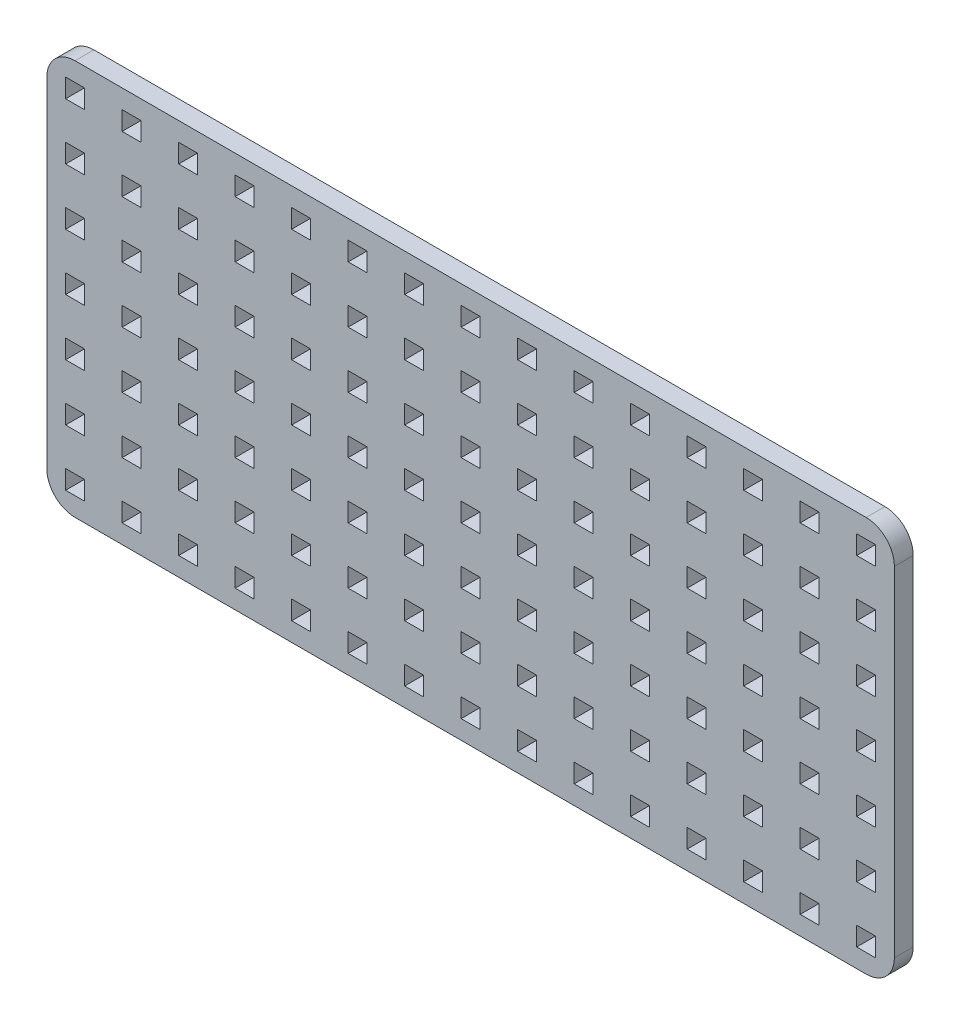
SolidWorks part; units mm, degrees
ref_plane "Alzado" through (0, 0, 0) normal (0, 0, 1) x (1, 0, 0)
ref_plane "Planta" through (0, 0, 0) normal (0, 1, 0) x (1, 0, 0)
ref_plane "Vista lateral" through (0, 0, 0) normal (1, 0, 0) x (0, 0, -1)
sketch "Model" plane through (0, 0, 0) normal (0, 0, 1) x (1, 0, 0)
  line L0 (11.9912, 291.2013) -> (11.9912, 288.2013)
  line L1 (14.9912, 291.2013) -> (11.9912, 291.2013)
  line L2 (14.9912, 288.2013) -> (14.9912, 291.2013)
  line L3 (11.9912, 288.2013) -> (14.9912, 288.2013)
  line L4 (20.9912, 291.2013) -> (20.9912, 288.2013)
  line L5 (23.9912, 291.2013) -> (20.9912, 291.2013)
  line L6 (23.9912, 288.2013) -> (23.9912, 291.2013)
  line L7 (20.9912, 288.2013) -> (23.9912, 288.2013)
  line L8 (29.9912, 291.2013) -> (29.9912, 288.2013)
  line L9 (32.9912, 291.2013) -> (29.9912, 291.2013)
  line L10 (32.9912, 288.2013) -> (32.9912, 291.2013)
  line L11 (29.9912, 288.2013) -> (32.9912, 288.2013)
  line L12 (38.9912, 291.2013) -> (38.9912, 288.2013)
  line L13 (41.9912, 291.2013) -> (38.9912, 291.2013)
  line L14 (41.9912, 288.2013) -> (41.9912, 291.2013)
  line L15 (38.9912, 288.2013) -> (41.9912, 288.2013)
  line L16 (47.9912, 291.2013) -> (47.9912, 288.2013)
  line L17 (50.9912, 291.2013) -> (47.9912, 291.2013)
  line L18 (50.9912, 288.2013) -> (50.9912, 291.2013)
  line L19 (47.9912, 288.2013) -> (50.9912, 288.2013)
  line L20 (56.9912, 291.2013) -> (56.9912, 288.2013)
  line L21 (59.9912, 291.2013) -> (56.9912, 291.2013)
  line L22 (59.9912, 288.2013) -> (59.9912, 291.2013)
  line L23 (56.9912, 288.2013) -> (59.9912, 288.2013)
  line L24 (65.9912, 291.2013) -> (65.9912, 288.2013)
  line L25 (68.9912, 291.2013) -> (65.9912, 291.2013)
  line L26 (68.9912, 288.2013) -> (68.9912, 291.2013)
  line L27 (65.9912, 288.2013) -> (68.9912, 288.2013)
  line L28 (74.9912, 291.2013) -> (74.9912, 288.2013)
  line L29 (77.9912, 291.2013) -> (74.9912, 291.2013)
  line L30 (77.9912, 288.2013) -> (77.9912, 291.2013)
  line L31 (74.9912, 288.2013) -> (77.9912, 288.2013)
  line L32 (83.9912, 291.2013) -> (83.9912, 288.2013)
  line L33 (86.9912, 291.2013) -> (83.9912, 291.2013)
  line L34 (86.9912, 288.2013) -> (86.9912, 291.2013)
  line L35 (83.9912, 288.2013) -> (86.9912, 288.2013)
  line L36 (92.9912, 291.2013) -> (92.9912, 288.2013)
  line L37 (95.9912, 291.2013) -> (92.9912, 291.2013)
  line L38 (95.9912, 288.2013) -> (95.9912, 291.2013)
  line L39 (92.9912, 288.2013) -> (95.9912, 288.2013)
  line L40 (101.9912, 291.2013) -> (101.9912, 288.2013)
  line L41 (104.9912, 291.2013) -> (101.9912, 291.2013)
  line L42 (104.9912, 288.2013) -> (104.9912, 291.2013)
  line L43 (101.9912, 288.2013) -> (104.9912, 288.2013)
  line L44 (110.9912, 291.2013) -> (110.9912, 288.2013)
  line L45 (113.9912, 291.2013) -> (110.9912, 291.2013)
  line L46 (113.9912, 288.2013) -> (113.9912, 291.2013)
  line L47 (110.9912, 288.2013) -> (113.9912, 288.2013)
  line L48 (119.9912, 291.2013) -> (119.9912, 288.2013)
  line L49 (122.9912, 291.2013) -> (119.9912, 291.2013)
  line L50 (122.9912, 288.2013) -> (122.9912, 291.2013)
  line L51 (119.9912, 288.2013) -> (122.9912, 288.2013)
  line L52 (128.9912, 291.2013) -> (128.9912, 288.2013)
  line L53 (131.9912, 291.2013) -> (128.9912, 291.2013)
  line L54 (131.9912, 288.2013) -> (131.9912, 291.2013)
  line L55 (128.9912, 288.2013) -> (131.9912, 288.2013)
  line L56 (137.9912, 291.2013) -> (137.9912, 288.2013)
  line L57 (140.9912, 291.2013) -> (137.9912, 291.2013)
  line L58 (140.9912, 288.2013) -> (140.9912, 291.2013)
  line L59 (137.9912, 288.2013) -> (140.9912, 288.2013)
  line L60 (11.9912, 282.2013) -> (11.9912, 279.2013)
  line L61 (14.9912, 282.2013) -> (11.9912, 282.2013)
  line L62 (14.9912, 279.2013) -> (14.9912, 282.2013)
  line L63 (11.9912, 279.2013) -> (14.9912, 279.2013)
  line L64 (20.9912, 282.2013) -> (20.9912, 279.2013)
  line L65 (23.9912, 282.2013) -> (20.9912, 282.2013)
  line L66 (23.9912, 279.2013) -> (23.9912, 282.2013)
  line L67 (20.9912, 279.2013) -> (23.9912, 279.2013)
  line L68 (29.9912, 282.2013) -> (29.9912, 279.2013)
  line L69 (32.9912, 282.2013) -> (29.9912, 282.2013)
  line L70 (32.9912, 279.2013) -> (32.9912, 282.2013)
  line L71 (29.9912, 279.2013) -> (32.9912, 279.2013)
  line L72 (38.9912, 282.2013) -> (38.9912, 279.2013)
  line L73 (41.9912, 282.2013) -> (38.9912, 282.2013)
  line L74 (41.9912, 279.2013) -> (41.9912, 282.2013)
  line L75 (38.9912, 279.2013) -> (41.9912, 279.2013)
  line L76 (47.9912, 282.2013) -> (47.9912, 279.2013)
  line L77 (50.9912, 282.2013) -> (47.9912, 282.2013)
  line L78 (50.9912, 279.2013) -> (50.9912, 282.2013)
  line L79 (47.9912, 279.2013) -> (50.9912, 279.2013)
  line L80 (56.9912, 282.2013) -> (56.9912, 279.2013)
  line L81 (59.9912, 282.2013) -> (56.9912, 282.2013)
  line L82 (59.9912, 279.2013) -> (59.9912, 282.2013)
  line L83 (56.9912, 279.2013) -> (59.9912, 279.2013)
  line L84 (65.9912, 282.2013) -> (65.9912, 279.2013)
  line L85 (68.9912, 282.2013) -> (65.9912, 282.2013)
  line L86 (68.9912, 279.2013) -> (68.9912, 282.2013)
  line L87 (65.9912, 279.2013) -> (68.9912, 279.2013)
  line L88 (74.9912, 282.2013) -> (74.9912, 279.2013)
  line L89 (77.9912, 282.2013) -> (74.9912, 282.2013)
  line L90 (77.9912, 279.2013) -> (77.9912, 282.2013)
  line L91 (74.9912, 279.2013) -> (77.9912, 279.2013)
  line L92 (83.9912, 282.2013) -> (83.9912, 279.2013)
  line L93 (86.9912, 282.2013) -> (83.9912, 282.2013)
  line L94 (86.9912, 279.2013) -> (86.9912, 282.2013)
  line L95 (83.9912, 279.2013) -> (86.9912, 279.2013)
  line L96 (92.9912, 282.2013) -> (92.9912, 279.2013)
  line L97 (95.9912, 282.2013) -> (92.9912, 282.2013)
  line L98 (95.9912, 279.2013) -> (95.9912, 282.2013)
  line L99 (92.9912, 279.2013) -> (95.9912, 279.2013)
  line L100 (101.9912, 282.2013) -> (101.9912, 279.2013)
  line L101 (104.9912, 282.2013) -> (101.9912, 282.2013)
  line L102 (104.9912, 279.2013) -> (104.9912, 282.2013)
  line L103 (101.9912, 279.2013) -> (104.9912, 279.2013)
  line L104 (110.9912, 282.2013) -> (110.9912, 279.2013)
  line L105 (113.9912, 282.2013) -> (110.9912, 282.2013)
  line L106 (113.9912, 279.2013) -> (113.9912, 282.2013)
  line L107 (110.9912, 279.2013) -> (113.9912, 279.2013)
  line L108 (119.9912, 282.2013) -> (119.9912, 279.2013)
  line L109 (122.9912, 282.2013) -> (119.9912, 282.2013)
  line L110 (122.9912, 279.2013) -> (122.9912, 282.2013)
  line L111 (119.9912, 279.2013) -> (122.9912, 279.2013)
  line L112 (128.9912, 282.2013) -> (128.9912, 279.2013)
  line L113 (131.9912, 282.2013) -> (128.9912, 282.2013)
  line L114 (131.9912, 279.2013) -> (131.9912, 282.2013)
  line L115 (128.9912, 279.2013) -> (131.9912, 279.2013)
  line L116 (137.9912, 282.2013) -> (137.9912, 279.2013)
  line L117 (140.9912, 282.2013) -> (137.9912, 282.2013)
  line L118 (140.9912, 279.2013) -> (140.9912, 282.2013)
  line L119 (137.9912, 279.2013) -> (140.9912, 279.2013)
  line L120 (11.9912, 273.2013) -> (11.9912, 270.2013)
  line L121 (14.9912, 273.2013) -> (11.9912, 273.2013)
  line L122 (14.9912, 270.2013) -> (14.9912, 273.2013)
  line L123 (11.9912, 270.2013) -> (14.9912, 270.2013)
  line L124 (20.9912, 273.2013) -> (20.9912, 270.2013)
  line L125 (23.9912, 273.2013) -> (20.9912, 273.2013)
  line L126 (23.9912, 270.2013) -> (23.9912, 273.2013)
  line L127 (20.9912, 270.2013) -> (23.9912, 270.2013)
  line L128 (29.9912, 273.2013) -> (29.9912, 270.2013)
  line L129 (32.9912, 273.2013) -> (29.9912, 273.2013)
  line L130 (32.9912, 270.2013) -> (32.9912, 273.2013)
  line L131 (29.9912, 270.2013) -> (32.9912, 270.2013)
  line L132 (38.9912, 273.2013) -> (38.9912, 270.2013)
  line L133 (41.9912, 273.2013) -> (38.9912, 273.2013)
  line L134 (41.9912, 270.2013) -> (41.9912, 273.2013)
  line L135 (38.9912, 270.2013) -> (41.9912, 270.2013)
  line L136 (47.9912, 273.2013) -> (47.9912, 270.2013)
  line L137 (50.9912, 273.2013) -> (47.9912, 273.2013)
  line L138 (50.9912, 270.2013) -> (50.9912, 273.2013)
  line L139 (47.9912, 270.2013) -> (50.9912, 270.2013)
  line L140 (56.9912, 273.2013) -> (56.9912, 270.2013)
  line L141 (59.9912, 273.2013) -> (56.9912, 273.2013)
  line L142 (59.9912, 270.2013) -> (59.9912, 273.2013)
  line L143 (56.9912, 270.2013) -> (59.9912, 270.2013)
  line L144 (65.9912, 273.2013) -> (65.9912, 270.2013)
  line L145 (68.9912, 273.2013) -> (65.9912, 273.2013)
  line L146 (68.9912, 270.2013) -> (68.9912, 273.2013)
  line L147 (65.9912, 270.2013) -> (68.9912, 270.2013)
  line L148 (74.9912, 273.2013) -> (74.9912, 270.2013)
  line L149 (77.9912, 273.2013) -> (74.9912, 273.2013)
  line L150 (77.9912, 270.2013) -> (77.9912, 273.2013)
  line L151 (74.9912, 270.2013) -> (77.9912, 270.2013)
  line L152 (83.9912, 273.2013) -> (83.9912, 270.2013)
  line L153 (86.9912, 273.2013) -> (83.9912, 273.2013)
  line L154 (86.9912, 270.2013) -> (86.9912, 273.2013)
  line L155 (83.9912, 270.2013) -> (86.9912, 270.2013)
  line L156 (92.9912, 273.2013) -> (92.9912, 270.2013)
  line L157 (95.9912, 273.2013) -> (92.9912, 273.2013)
  line L158 (95.9912, 270.2013) -> (95.9912, 273.2013)
  line L159 (92.9912, 270.2013) -> (95.9912, 270.2013)
  line L160 (101.9912, 273.2013) -> (101.9912, 270.2013)
  line L161 (104.9912, 273.2013) -> (101.9912, 273.2013)
  line L162 (104.9912, 270.2013) -> (104.9912, 273.2013)
  line L163 (101.9912, 270.2013) -> (104.9912, 270.2013)
  line L164 (110.9912, 273.2013) -> (110.9912, 270.2013)
  line L165 (113.9912, 273.2013) -> (110.9912, 273.2013)
  line L166 (113.9912, 270.2013) -> (113.9912, 273.2013)
  line L167 (110.9912, 270.2013) -> (113.9912, 270.2013)
  line L168 (119.9912, 273.2013) -> (119.9912, 270.2013)
  line L169 (122.9912, 273.2013) -> (119.9912, 273.2013)
  line L170 (122.9912, 270.2013) -> (122.9912, 273.2013)
  line L171 (119.9912, 270.2013) -> (122.9912, 270.2013)
  line L172 (128.9912, 273.2013) -> (128.9912, 270.2013)
  line L173 (131.9912, 273.2013) -> (128.9912, 273.2013)
  line L174 (131.9912, 270.2013) -> (131.9912, 273.2013)
  line L175 (128.9912, 270.2013) -> (131.9912, 270.2013)
  line L176 (137.9912, 273.2013) -> (137.9912, 270.2013)
  line L177 (140.9912, 273.2013) -> (137.9912, 273.2013)
  line L178 (140.9912, 270.2013) -> (140.9912, 273.2013)
  line L179 (137.9912, 270.2013) -> (140.9912, 270.2013)
  line L180 (11.9912, 264.2013) -> (11.9912, 261.2013)
  line L181 (14.9912, 264.2013) -> (11.9912, 264.2013)
  line L182 (14.9912, 261.2013) -> (14.9912, 264.2013)
  line L183 (11.9912, 261.2013) -> (14.9912, 261.2013)
  line L184 (20.9912, 264.2013) -> (20.9912, 261.2013)
  line L185 (23.9912, 264.2013) -> (20.9912, 264.2013)
  line L186 (23.9912, 261.2013) -> (23.9912, 264.2013)
  line L187 (20.9912, 261.2013) -> (23.9912, 261.2013)
  line L188 (29.9912, 264.2013) -> (29.9912, 261.2013)
  line L189 (32.9912, 264.2013) -> (29.9912, 264.2013)
  line L190 (32.9912, 261.2013) -> (32.9912, 264.2013)
  line L191 (29.9912, 261.2013) -> (32.9912, 261.2013)
  line L192 (38.9912, 264.2013) -> (38.9912, 261.2013)
  line L193 (41.9912, 264.2013) -> (38.9912, 264.2013)
  line L194 (41.9912, 261.2013) -> (41.9912, 264.2013)
  line L195 (38.9912, 261.2013) -> (41.9912, 261.2013)
  line L196 (47.9912, 264.2013) -> (47.9912, 261.2013)
  line L197 (50.9912, 264.2013) -> (47.9912, 264.2013)
  line L198 (50.9912, 261.2013) -> (50.9912, 264.2013)
  line L199 (47.9912, 261.2013) -> (50.9912, 261.2013)
  line L200 (56.9912, 264.2013) -> (56.9912, 261.2013)
  line L201 (59.9912, 264.2013) -> (56.9912, 264.2013)
  line L202 (59.9912, 261.2013) -> (59.9912, 264.2013)
  line L203 (56.9912, 261.2013) -> (59.9912, 261.2013)
  line L204 (65.9912, 264.2013) -> (65.9912, 261.2013)
  line L205 (68.9912, 264.2013) -> (65.9912, 264.2013)
  line L206 (68.9912, 261.2013) -> (68.9912, 264.2013)
  line L207 (65.9912, 261.2013) -> (68.9912, 261.2013)
  line L208 (74.9912, 264.2013) -> (74.9912, 261.2013)
  line L209 (77.9912, 264.2013) -> (74.9912, 264.2013)
  line L210 (77.9912, 261.2013) -> (77.9912, 264.2013)
  line L211 (74.9912, 261.2013) -> (77.9912, 261.2013)
  line L212 (83.9912, 264.2013) -> (83.9912, 261.2013)
  line L213 (86.9912, 264.2013) -> (83.9912, 264.2013)
  line L214 (86.9912, 261.2013) -> (86.9912, 264.2013)
  line L215 (83.9912, 261.2013) -> (86.9912, 261.2013)
  line L216 (92.9912, 264.2013) -> (92.9912, 261.2013)
  line L217 (95.9912, 264.2013) -> (92.9912, 264.2013)
  line L218 (95.9912, 261.2013) -> (95.9912, 264.2013)
  line L219 (92.9912, 261.2013) -> (95.9912, 261.2013)
  line L220 (101.9912, 264.2013) -> (101.9912, 261.2013)
  line L221 (104.9912, 264.2013) -> (101.9912, 264.2013)
  line L222 (104.9912, 261.2013) -> (104.9912, 264.2013)
  line L223 (101.9912, 261.2013) -> (104.9912, 261.2013)
  line L224 (110.9912, 264.2013) -> (110.9912, 261.2013)
  line L225 (113.9912, 264.2013) -> (110.9912, 264.2013)
  line L226 (113.9912, 261.2013) -> (113.9912, 264.2013)
  line L227 (110.9912, 261.2013) -> (113.9912, 261.2013)
  line L228 (119.9912, 264.2013) -> (119.9912, 261.2013)
  line L229 (122.9912, 264.2013) -> (119.9912, 264.2013)
  line L230 (122.9912, 261.2013) -> (122.9912, 264.2013)
  line L231 (119.9912, 261.2013) -> (122.9912, 261.2013)
  line L232 (128.9912, 264.2013) -> (128.9912, 261.2013)
  line L233 (131.9912, 264.2013) -> (128.9912, 264.2013)
  line L234 (131.9912, 261.2013) -> (131.9912, 264.2013)
  line L235 (128.9912, 261.2013) -> (131.9912, 261.2013)
  line L236 (137.9912, 264.2013) -> (137.9912, 261.2013)
  line L237 (140.9912, 264.2013) -> (137.9912, 264.2013)
  line L238 (140.9912, 261.2013) -> (140.9912, 264.2013)
  line L239 (137.9912, 261.2013) -> (140.9912, 261.2013)
  line L240 (11.9912, 255.2013) -> (11.9912, 252.2013)
  line L241 (14.9912, 255.2013) -> (11.9912, 255.2013)
  line L242 (14.9912, 252.2013) -> (14.9912, 255.2013)
  line L243 (11.9912, 252.2013) -> (14.9912, 252.2013)
  line L244 (20.9912, 255.2013) -> (20.9912, 252.2013)
  line L245 (23.9912, 255.2013) -> (20.9912, 255.2013)
  line L246 (23.9912, 252.2013) -> (23.9912, 255.2013)
  line L247 (20.9912, 252.2013) -> (23.9912, 252.2013)
  line L248 (29.9912, 255.2013) -> (29.9912, 252.2013)
  line L249 (32.9912, 255.2013) -> (29.9912, 255.2013)
  line L250 (32.9912, 252.2013) -> (32.9912, 255.2013)
  line L251 (29.9912, 252.2013) -> (32.9912, 252.2013)
  line L252 (38.9912, 255.2013) -> (38.9912, 252.2013)
  line L253 (41.9912, 255.2013) -> (38.9912, 255.2013)
  line L254 (41.9912, 252.2013) -> (41.9912, 255.2013)
  line L255 (38.9912, 252.2013) -> (41.9912, 252.2013)
  line L256 (47.9912, 255.2013) -> (47.9912, 252.2013)
  line L257 (50.9912, 255.2013) -> (47.9912, 255.2013)
  line L258 (50.9912, 252.2013) -> (50.9912, 255.2013)
  line L259 (47.9912, 252.2013) -> (50.9912, 252.2013)
  line L260 (56.9912, 255.2013) -> (56.9912, 252.2013)
  line L261 (59.9912, 255.2013) -> (56.9912, 255.2013)
  line L262 (59.9912, 252.2013) -> (59.9912, 255.2013)
  line L263 (56.9912, 252.2013) -> (59.9912, 252.2013)
  line L264 (65.9912, 255.2013) -> (65.9912, 252.2013)
  line L265 (68.9912, 255.2013) -> (65.9912, 255.2013)
  line L266 (68.9912, 252.2013) -> (68.9912, 255.2013)
  line L267 (65.9912, 252.2013) -> (68.9912, 252.2013)
  line L268 (74.9912, 255.2013) -> (74.9912, 252.2013)
  line L269 (77.9912, 255.2013) -> (74.9912, 255.2013)
  line L270 (77.9912, 252.2013) -> (77.9912, 255.2013)
  line L271 (74.9912, 252.2013) -> (77.9912, 252.2013)
  line L272 (83.9912, 255.2013) -> (83.9912, 252.2013)
  line L273 (86.9912, 255.2013) -> (83.9912, 255.2013)
  line L274 (86.9912, 252.2013) -> (86.9912, 255.2013)
  line L275 (83.9912, 252.2013) -> (86.9912, 252.2013)
  line L276 (92.9912, 255.2013) -> (92.9912, 252.2013)
  line L277 (95.9912, 255.2013) -> (92.9912, 255.2013)
  line L278 (95.9912, 252.2013) -> (95.9912, 255.2013)
  line L279 (92.9912, 252.2013) -> (95.9912, 252.2013)
  line L280 (101.9912, 255.2013) -> (101.9912, 252.2013)
  line L281 (104.9912, 255.2013) -> (101.9912, 255.2013)
  line L282 (104.9912, 252.2013) -> (104.9912, 255.2013)
  line L283 (101.9912, 252.2013) -> (104.9912, 252.2013)
  line L284 (110.9912, 255.2013) -> (110.9912, 252.2013)
  line L285 (113.9912, 255.2013) -> (110.9912, 255.2013)
  line L286 (113.9912, 252.2013) -> (113.9912, 255.2013)
  line L287 (110.9912, 252.2013) -> (113.9912, 252.2013)
  line L288 (119.9912, 255.2013) -> (119.9912, 252.2013)
  line L289 (122.9912, 255.2013) -> (119.9912, 255.2013)
  line L290 (122.9912, 252.2013) -> (122.9912, 255.2013)
  line L291 (119.9912, 252.2013) -> (122.9912, 252.2013)
  line L292 (128.9912, 255.2013) -> (128.9912, 252.2013)
  line L293 (131.9912, 255.2013) -> (128.9912, 255.2013)
  line L294 (131.9912, 252.2013) -> (131.9912, 255.2013)
  line L295 (128.9912, 252.2013) -> (131.9912, 252.2013)
  line L296 (137.9912, 255.2013) -> (137.9912, 252.2013)
  line L297 (140.9912, 255.2013) -> (137.9912, 255.2013)
  line L298 (140.9912, 252.2013) -> (140.9912, 255.2013)
  line L299 (137.9912, 252.2013) -> (140.9912, 252.2013)
  line L300 (11.9912, 246.2013) -> (11.9912, 243.2013)
  line L301 (14.9912, 246.2013) -> (11.9912, 246.2013)
  line L302 (14.9912, 243.2013) -> (14.9912, 246.2013)
  line L303 (11.9912, 243.2013) -> (14.9912, 243.2013)
  line L304 (20.9912, 246.2013) -> (20.9912, 243.2013)
  line L305 (23.9912, 246.2013) -> (20.9912, 246.2013)
  line L306 (23.9912, 243.2013) -> (23.9912, 246.2013)
  line L307 (20.9912, 243.2013) -> (23.9912, 243.2013)
  line L308 (29.9912, 246.2013) -> (29.9912, 243.2013)
  line L309 (32.9912, 246.2013) -> (29.9912, 246.2013)
  line L310 (32.9912, 243.2013) -> (32.9912, 246.2013)
  line L311 (29.9912, 243.2013) -> (32.9912, 243.2013)
  line L312 (38.9912, 246.2013) -> (38.9912, 243.2013)
  line L313 (41.9912, 246.2013) -> (38.9912, 246.2013)
  line L314 (41.9912, 243.2013) -> (41.9912, 246.2013)
  line L315 (38.9912, 243.2013) -> (41.9912, 243.2013)
  line L316 (47.9912, 246.2013) -> (47.9912, 243.2013)
  line L317 (50.9912, 246.2013) -> (47.9912, 246.2013)
  line L318 (50.9912, 243.2013) -> (50.9912, 246.2013)
  line L319 (47.9912, 243.2013) -> (50.9912, 243.2013)
  line L320 (56.9912, 246.2013) -> (56.9912, 243.2013)
  line L321 (59.9912, 246.2013) -> (56.9912, 246.2013)
  line L322 (59.9912, 243.2013) -> (59.9912, 246.2013)
  line L323 (56.9912, 243.2013) -> (59.9912, 243.2013)
  line L324 (65.9912, 246.2013) -> (65.9912, 243.2013)
  line L325 (68.9912, 246.2013) -> (65.9912, 246.2013)
  line L326 (68.9912, 243.2013) -> (68.9912, 246.2013)
  line L327 (65.9912, 243.2013) -> (68.9912, 243.2013)
  line L328 (74.9912, 246.2013) -> (74.9912, 243.2013)
  line L329 (77.9912, 246.2013) -> (74.9912, 246.2013)
  line L330 (77.9912, 243.2013) -> (77.9912, 246.2013)
  line L331 (74.9912, 243.2013) -> (77.9912, 243.2013)
  line L332 (83.9912, 246.2013) -> (83.9912, 243.2013)
  line L333 (86.9912, 246.2013) -> (83.9912, 246.2013)
  line L334 (86.9912, 243.2013) -> (86.9912, 246.2013)
  line L335 (83.9912, 243.2013) -> (86.9912, 243.2013)
  line L336 (92.9912, 246.2013) -> (92.9912, 243.2013)
  line L337 (95.9912, 246.2013) -> (92.9912, 246.2013)
  line L338 (95.9912, 243.2013) -> (95.9912, 246.2013)
  line L339 (92.9912, 243.2013) -> (95.9912, 243.2013)
  line L340 (101.9912, 246.2013) -> (101.9912, 243.2013)
  line L341 (104.9912, 246.2013) -> (101.9912, 246.2013)
  line L342 (104.9912, 243.2013) -> (104.9912, 246.2013)
  line L343 (101.9912, 243.2013) -> (104.9912, 243.2013)
  line L344 (110.9912, 246.2013) -> (110.9912, 243.2013)
  line L345 (113.9912, 246.2013) -> (110.9912, 246.2013)
  line L346 (113.9912, 243.2013) -> (113.9912, 246.2013)
  line L347 (110.9912, 243.2013) -> (113.9912, 243.2013)
  line L348 (119.9912, 246.2013) -> (119.9912, 243.2013)
  line L349 (122.9912, 246.2013) -> (119.9912, 246.2013)
  line L350 (122.9912, 243.2013) -> (122.9912, 246.2013)
  line L351 (119.9912, 243.2013) -> (122.9912, 243.2013)
  line L352 (128.9912, 246.2013) -> (128.9912, 243.2013)
  line L353 (131.9912, 246.2013) -> (128.9912, 246.2013)
  line L354 (131.9912, 243.2013) -> (131.9912, 246.2013)
  line L355 (128.9912, 243.2013) -> (131.9912, 243.2013)
  line L356 (137.9912, 246.2013) -> (137.9912, 243.2013)
  line L357 (140.9912, 246.2013) -> (137.9912, 246.2013)
  line L358 (140.9912, 243.2013) -> (140.9912, 246.2013)
  line L359 (137.9912, 243.2013) -> (140.9912, 243.2013)
  line L360 (11.9912, 237.2013) -> (11.9912, 234.2013)
  line L361 (14.9912, 237.2013) -> (11.9912, 237.2013)
  line L362 (14.9912, 234.2013) -> (14.9912, 237.2013)
  line L363 (11.9912, 234.2013) -> (14.9912, 234.2013)
  line L364 (20.9912, 237.2013) -> (20.9912, 234.2013)
  line L365 (23.9912, 237.2013) -> (20.9912, 237.2013)
  line L366 (23.9912, 234.2013) -> (23.9912, 237.2013)
  line L367 (20.9912, 234.2013) -> (23.9912, 234.2013)
  line L368 (29.9912, 237.2013) -> (29.9912, 234.2013)
  line L369 (32.9912, 237.2013) -> (29.9912, 237.2013)
  line L370 (32.9912, 234.2013) -> (32.9912, 237.2013)
  line L371 (29.9912, 234.2013) -> (32.9912, 234.2013)
  line L372 (38.9912, 237.2013) -> (38.9912, 234.2013)
  line L373 (41.9912, 237.2013) -> (38.9912, 237.2013)
  line L374 (41.9912, 234.2013) -> (41.9912, 237.2013)
  line L375 (38.9912, 234.2013) -> (41.9912, 234.2013)
  line L376 (47.9912, 237.2013) -> (47.9912, 234.2013)
  line L377 (50.9912, 237.2013) -> (47.9912, 237.2013)
  line L378 (50.9912, 234.2013) -> (50.9912, 237.2013)
  line L379 (47.9912, 234.2013) -> (50.9912, 234.2013)
  line L380 (56.9912, 237.2013) -> (56.9912, 234.2013)
  line L381 (59.9912, 237.2013) -> (56.9912, 237.2013)
  line L382 (59.9912, 234.2013) -> (59.9912, 237.2013)
  line L383 (56.9912, 234.2013) -> (59.9912, 234.2013)
  line L384 (65.9912, 237.2013) -> (65.9912, 234.2013)
  line L385 (68.9912, 237.2013) -> (65.9912, 237.2013)
  line L386 (68.9912, 234.2013) -> (68.9912, 237.2013)
  line L387 (65.9912, 234.2013) -> (68.9912, 234.2013)
  line L388 (74.9912, 237.2013) -> (74.9912, 234.2013)
  line L389 (77.9912, 237.2013) -> (74.9912, 237.2013)
  line L390 (77.9912, 234.2013) -> (77.9912, 237.2013)
  line L391 (74.9912, 234.2013) -> (77.9912, 234.2013)
  line L392 (83.9912, 237.2013) -> (83.9912, 234.2013)
  line L393 (86.9912, 237.2013) -> (83.9912, 237.2013)
  line L394 (86.9912, 234.2013) -> (86.9912, 237.2013)
  line L395 (83.9912, 234.2013) -> (86.9912, 234.2013)
  line L396 (92.9912, 237.2013) -> (92.9912, 234.2013)
  line L397 (95.9912, 237.2013) -> (92.9912, 237.2013)
  line L398 (95.9912, 234.2013) -> (95.9912, 237.2013)
  line L399 (92.9912, 234.2013) -> (95.9912, 234.2013)
  line L400 (101.9912, 237.2013) -> (101.9912, 234.2013)
  line L401 (104.9912, 237.2013) -> (101.9912, 237.2013)
  line L402 (104.9912, 234.2013) -> (104.9912, 237.2013)
  line L403 (101.9912, 234.2013) -> (104.9912, 234.2013)
  line L404 (110.9912, 237.2013) -> (110.9912, 234.2013)
  line L405 (113.9912, 237.2013) -> (110.9912, 237.2013)
  line L406 (113.9912, 234.2013) -> (113.9912, 237.2013)
  line L407 (110.9912, 234.2013) -> (113.9912, 234.2013)
  line L408 (119.9912, 237.2013) -> (119.9912, 234.2013)
  line L409 (122.9912, 237.2013) -> (119.9912, 237.2013)
  line L410 (122.9912, 234.2013) -> (122.9912, 237.2013)
  line L411 (119.9912, 234.2013) -> (122.9912, 234.2013)
  line L412 (128.9912, 237.2013) -> (128.9912, 234.2013)
  line L413 (131.9912, 237.2013) -> (128.9912, 237.2013)
  line L414 (131.9912, 234.2013) -> (131.9912, 237.2013)
  line L415 (128.9912, 234.2013) -> (131.9912, 234.2013)
  line L416 (137.9912, 237.2013) -> (137.9912, 234.2013)
  line L417 (140.9912, 237.2013) -> (137.9912, 237.2013)
  line L418 (140.9912, 234.2013) -> (140.9912, 237.2013)
  line L419 (137.9912, 234.2013) -> (140.9912, 234.2013)
  line L420 (143.9912, 235.7041) -> (143.9912, 289.7013)
  line L421 (139.4912, 294.2013) -> (13.4912, 294.2013)
  line L422 (8.9912, 289.7013) -> (8.9912, 235.7041)
  line L423 (13.4912, 231.2041) -> (139.4912, 231.2041)
  arc A0 (143.9912, 289.7013) -> (139.4912, 294.2013) centre (139.4912, 289.7013) ccw
  arc A1 (139.4912, 231.2041) -> (143.9912, 235.7041) centre (139.4912, 235.7041) ccw
  arc A2 (13.4912, 294.2013) -> (8.9912, 289.7013) centre (13.4912, 289.7013) ccw
  arc A3 (8.9912, 235.7041) -> (13.4912, 231.2041) centre (13.4912, 235.7041) ccw
extrude "Saliente-Extruir1" add sketch "Model" along normal blind 3
